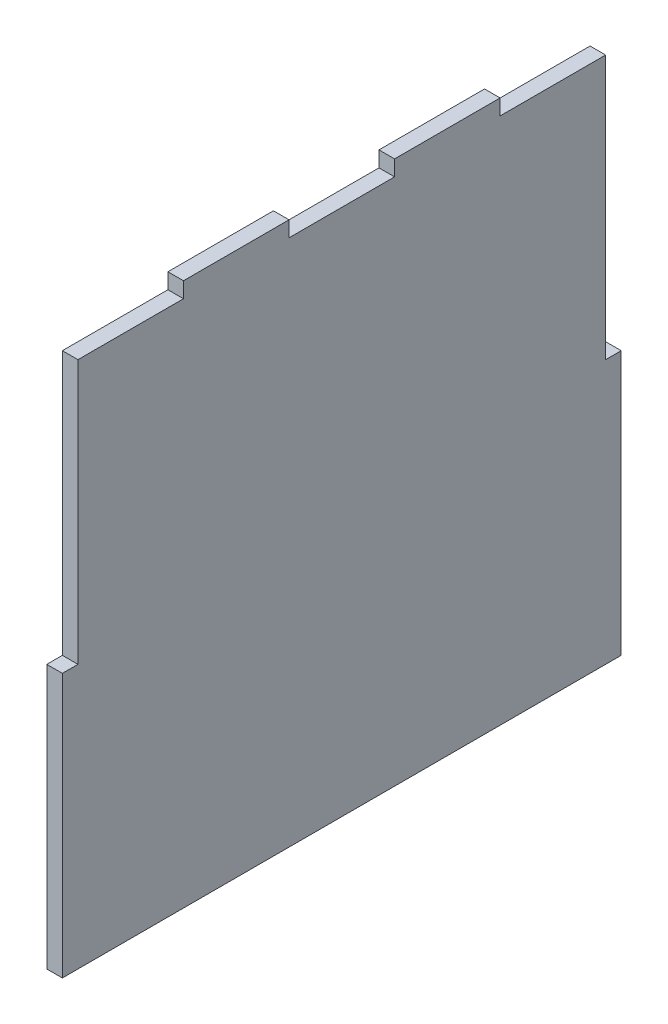
SolidWorks part; units mm, degrees
ref_plane "Alzado" through (0, 0, 0) normal (0, 0, 1) x (1, 0, 0)
ref_plane "Planta" through (0, 0, 0) normal (0, 1, 0) x (1, 0, 0)
ref_plane "Vista lateral" through (0, 0, 0) normal (1, 0, 0) x (0, 0, -1)
sketch "Croquis1" plane through (0, 0, 0) normal (1, 0, 0) x (0, 0, -1)
  line L0 (0, 0) -> (0, 50.8)
  line L1 (0, 50.8) -> (3, 50.8)
  line L2 (3, 50.8) -> (3, 101.6)
  line L3 (3, 101.6) -> (23.32, 101.6)
  line L4 (23.32, 101.6) -> (23.32, 104.6)
  line L5 (23.32, 104.6) -> (43.64, 104.6)
  line L6 (43.64, 104.6) -> (43.64, 101.6)
  line L7 (43.64, 101.6) -> (63.96, 101.6)
  line L8 (63.96, 101.6) -> (63.96, 104.6)
  line L9 (63.96, 104.6) -> (84.28, 104.6)
  line L10 (84.28, 104.6) -> (84.28, 101.6)
  line L11 (84.28, 101.6) -> (104.6, 101.6)
  line L12 (104.6, 101.6) -> (104.6, 50.8)
  line L13 (104.6, 50.8) -> (107.6, 50.8)
  line L14 (107.6, 50.8) -> (107.6, 0)
  line L15 (107.6, 0) -> (0, 0)
  point P17 (0, 0)
  point P18 (107.6, 43.5262)
  dimension "D1" = 107.6
  dimension "D2" = 3
  dimension "D3" = 50.8
  dimension "D4" = 50.8
  dimension "D5" = 20.32
  dimension "D6" = 3
  dimension "D7" = 20.32
  dimension "D8" = 20.32
  dimension "D9" = 50.8
extrude "Saliente-Extruir1" add sketch "Croquis1" along normal blind 3
